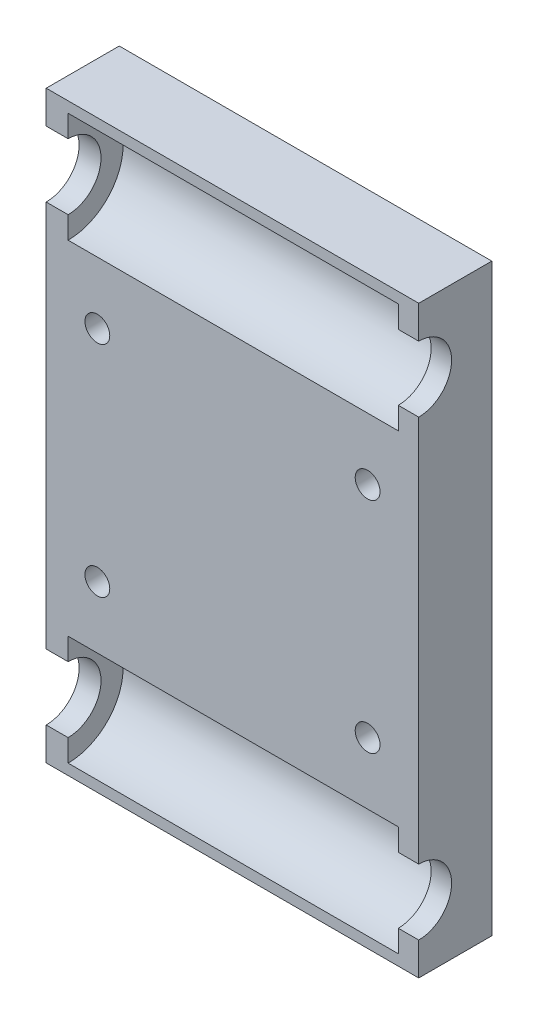
SolidWorks part; units mm, degrees
other "Markup1"
sketch "Sketch5" plane through (0, 0, 0) normal (-0.0371, -0.0717, -0.9967) x (-0.9993, 0.0007, 0.0371)
ref_plane "Front Plane" through (0, 0, 0) normal (0, 0, 1) x (1, 0, 0)
ref_plane "Top Plane" through (0, 0, 0) normal (0, 1, 0) x (1, 0, 0)
ref_plane "Right Plane" through (0, 0, 0) normal (1, 0, 0) x (0, 0, -1)
sketch "Sketch1" plane through (0, 0, 0) normal (0, 0, 1) x (1, 0, 0)
  line L1 (0, 0) -> (51, 0)
  line L2 (0, 0) -> (0, 80)
  line L3 (0, 80) -> (51, 80)
  line L4 (51, 0) -> (51, 80)
  circle A0 centre (7, 55) radius 1.7
  circle A1 centre (44, 55) radius 1.7
  circle A2 centre (7, 25) radius 1.7
  circle A3 centre (44, 25) radius 1.7
  dimension "D6" = 3.4
  dimension "D1" = 51
  dimension "D2" = 80
  dimension "D3" = 7
  dimension "D4" = 7
  dimension "D5" = 25
  dimension "D7" = 25
extrude "Boss-Extrude1" add sketch "Sketch1" along normal blind 10
ref_plane "Plane1" through (3, 0, 0) normal (-1, 0, 0) x (0, 0, 1)
sketch "Sketch2" plane through (3, 0, 0) normal (-1, 0, 0) x (0, 0, 1)
  line L0 (10, 80) -> (10, 0) construction
  line L1 (10, 80) -> (0, 80) construction
  line L2 (10, 0) -> (0, 0) construction
  circle A0 centre (10, 71) radius 7.525
  circle A1 centre (10, 9) radius 7.525
  dimension "D2" = 15.05
  dimension "D3" = 15.05
  dimension "D1" = 9
  dimension "D4" = 9
extrude "Cut-Extrude1" cut sketch "Sketch2" against normal blind 45.2
sketch "Sketch3" plane through (0, 0, 0) normal (-1, 0, 0) x (0, 0, 1)
  line L0 (10, 80) -> (10, 0) construction
  circle A0 centre (10, 71) radius 4.5
  circle A1 centre (10, 9) radius 4.5
  arc A2 (10, 78.525) -> (10, 63.475) centre (10, 71) ccw construction
  arc A3 (10, 16.525) -> (10, 1.475) centre (10, 9) ccw construction
  dimension "D1" = 9
  dimension "D2" = 9
extrude "Cut-Extrude2" cut sketch "Sketch3" against normal through all
sketch "Sketch4" plane through (0, 0, 0) normal (0, 0, -1) x (-1, 0, 0)
  circle A0 centre (-44, 55) radius 3
  circle A1 centre (-7, 55) radius 3
  circle A2 centre (-7, 25) radius 3
  circle A3 centre (-44, 25) radius 3
  dimension "D1" = 6
extrude "Cut-Extrude3" cut sketch "Sketch4" against normal blind 3
